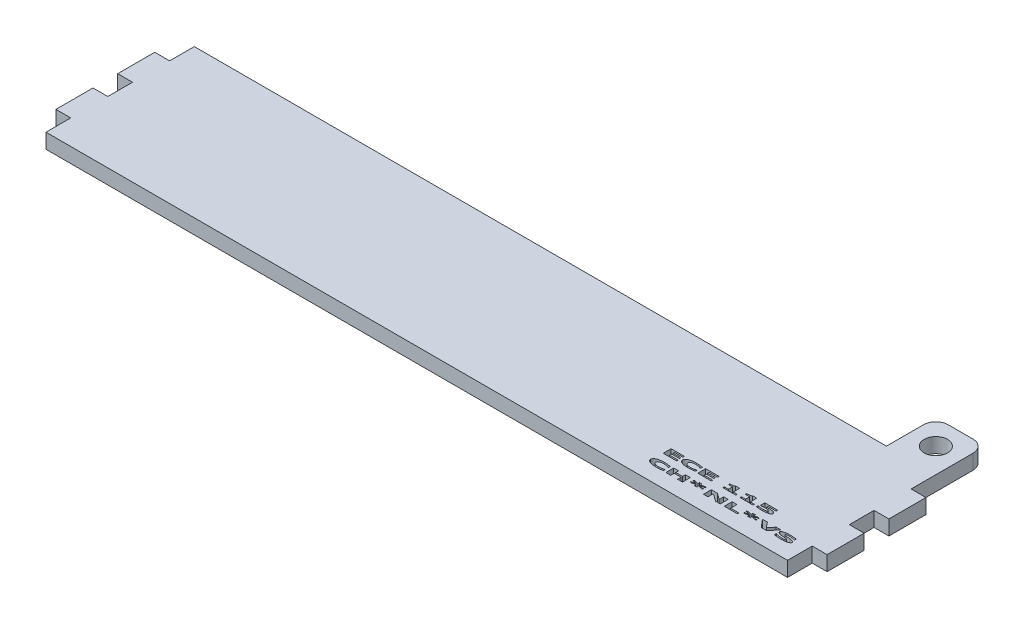
SolidWorks part; units mm, degrees
ref_plane "Front Plane" through (0, 0, 0) normal (0, 0, 1) x (1, 0, 0)
ref_plane "Top Plane" through (0, 0, 0) normal (0, 1, 0) x (1, 0, 0)
ref_plane "Right Plane" through (0, 0, 0) normal (1, 0, 0) x (0, 0, -1)
sketch "Sketch1" plane through (0, 0, 0) normal (0, 1, 0) x (1, 0, 0)
  line L0 (-153.929, 40.6069) -> (-153.929, 30.6069)
  line L1 (-153.929, 65.6069) -> (126.071, 65.6069)
  line L2 (-153.929, 65.6069) -> (-153.929, 55.6069)
  line L3 (-153.929, 5.6069) -> (146.071, 5.6069)
  line L4 (146.071, 65.6069) -> (146.071, 55.6069)
  line L6 (126.071, 65.6069) -> (126.071, 85.6069)
  line L7 (126.071, 85.6069) -> (146.071, 85.6069)
  line L8 (146.071, 65.6069) -> (146.071, 85.6069)
  line L9 (-153.929, 55.6069) -> (-159.929, 55.6069)
  line L11 (-153.929, 40.6069) -> (-159.929, 40.6069)
  line L12 (-159.929, 55.6069) -> (-159.929, 40.6069)
  line L13 (-153.929, 30.6069) -> (-159.929, 30.6069)
  line L15 (-153.929, 15.6069) -> (-159.929, 15.6069)
  line L16 (-159.929, 30.6069) -> (-159.929, 15.6069)
  line L17 (146.071, 55.6069) -> (152.071, 55.6069)
  line L19 (146.071, 40.6069) -> (152.071, 40.6069)
  line L20 (152.071, 55.6069) -> (152.071, 40.6069)
  line L21 (146.071, 30.6069) -> (152.071, 30.6069)
  line L23 (146.071, 15.6069) -> (152.071, 15.6069)
  line L24 (152.071, 30.6069) -> (152.071, 15.6069)
  line L25 (-153.929, 15.6069) -> (-153.929, 5.6069)
  line L26 (146.071, 40.6069) -> (146.071, 30.6069)
  line L27 (146.071, 15.6069) -> (146.071, 5.6069)
  dimension "D1" = 300
  dimension "D2" = 60
  dimension "D3" = 20
  dimension "D4" = 20
  dimension "D5" = 6
  dimension "D6" = 6
  dimension "D7" = 10
  dimension "D8" = 10
  dimension "D9" = 15
  dimension "D10" = 15
  dimension "D11" = 15
  dimension "D12" = 15
  dimension "D13" = 10
  dimension "D14" = 10
  dimension "D15" = 6
  dimension "D16" = 6
extrude "Boss-Extrude1" add sketch "Sketch1" along normal blind 6
sketch "Sketch2" plane through (0, 6, 0) normal (0, 1, 0) x (1, 0, 0)
  line L0 (126.071, 65.6069) -> (146.071, 65.6069) construction
  line L1 (146.071, 55.6069) -> (146.071, 85.6069) construction
  line L2 (146.071, 65.6069) -> (126.071, 85.6069) construction
  line L3 (126.071, 65.6069) -> (146.071, 85.6069) construction
  circle A0 centre (136.071, 75.6069) radius 4.75
  dimension "D1" = 9.5
extrude "Cut-Extrude1" cut sketch "Sketch2" against normal blind 6
fillet "Fillet2" radius 5 2 edges at (146.071, 3, -85.6069) (126.071, 3, -85.6069)
sketch "Sketch3" plane through (0, 6, 0) normal (0, 1, 0) x (1, 0, 0)
  text T0 "ECE 115\r\nCH*NL*VS" font "Tahoma" height 3.175
extrude "Cut-Extrude2" cut sketch "Sketch3" against normal blind 10
